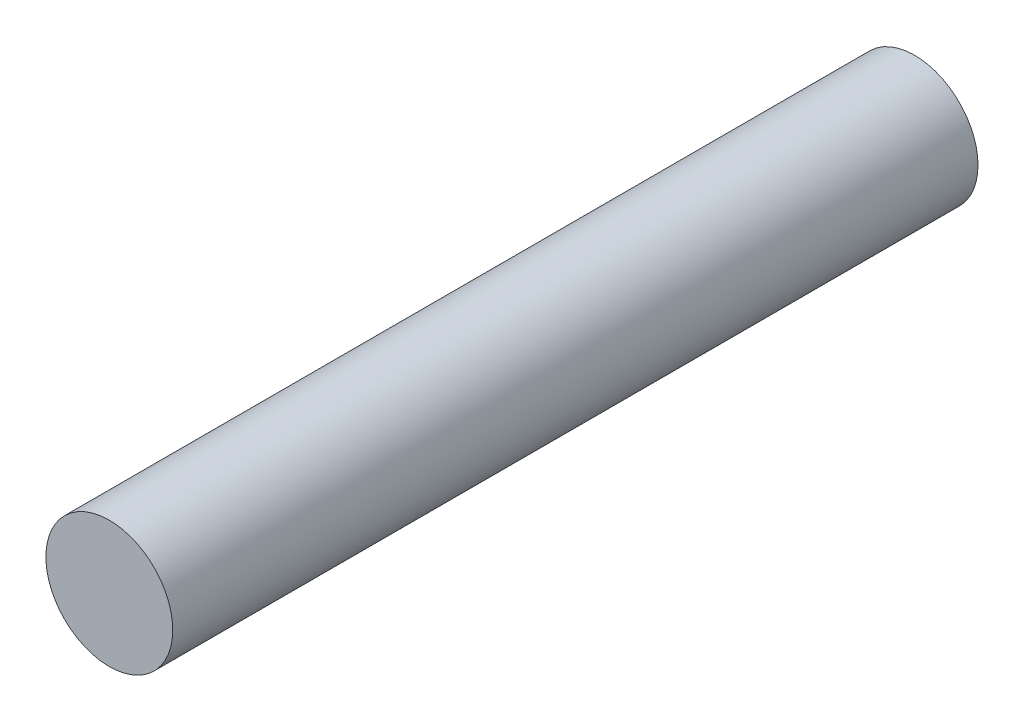
SolidWorks part; units mm, degrees
ref_plane "Front Plane" through (0, 0, 0) normal (0, 0, 1) x (1, 0, 0)
ref_plane "Top Plane" through (0, 0, 0) normal (0, 1, 0) x (1, 0, 0)
ref_plane "Right Plane" through (0, 0, 0) normal (1, 0, 0) x (0, 0, -1)
sketch "Sketch1" plane through (0, 0, 0) normal (0, 0, 1) x (1, 0, 0)
  circle A0 centre (0, 0) radius 20
  dimension "D1" = 40
extrude "Boss-Extrude1" add sketch "Sketch1" along normal blind 254
